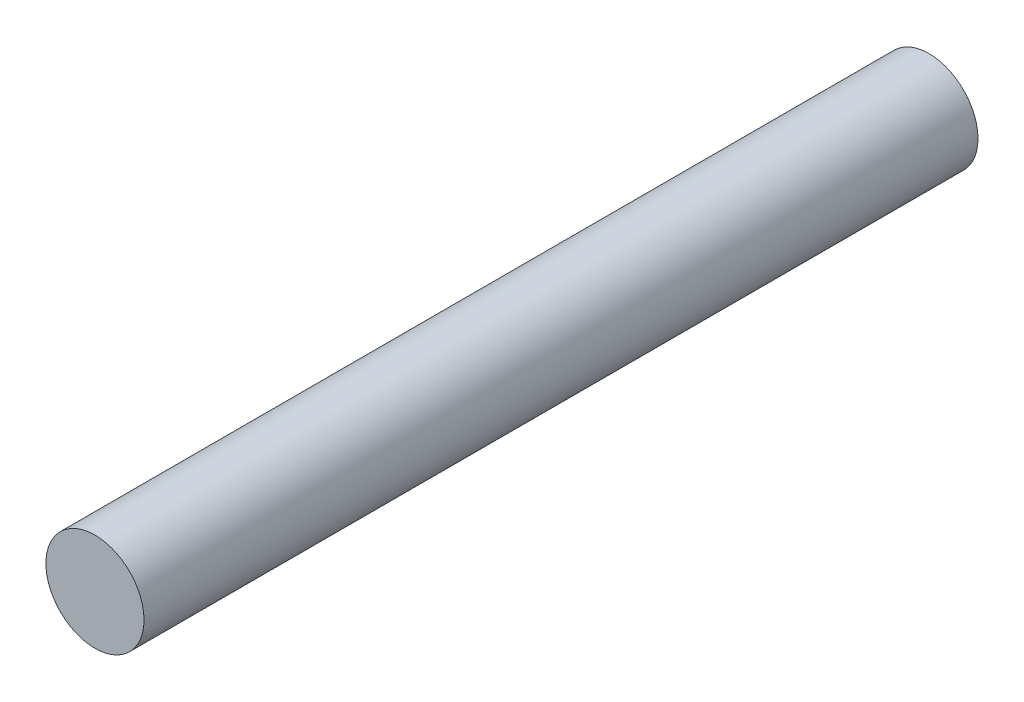
SolidWorks part; units mm, degrees
ref_plane "Front Plane" through (0, 0, 0) normal (0, 0, 1) x (1, 0, 0)
ref_plane "Top Plane" through (0, 0, 0) normal (0, 1, 0) x (1, 0, 0)
ref_plane "Right Plane" through (0, 0, 0) normal (1, 0, 0) x (0, 0, -1)
sketch "Sketch1" plane through (0, 0, 0) normal (0, 0, 1) x (1, 0, 0)
  circle A0 centre (0, 0) radius 12.7
  dimension "D1" = 25.4
extrude "Boss-Extrude1" add sketch "Sketch1" along normal blind 215.9
